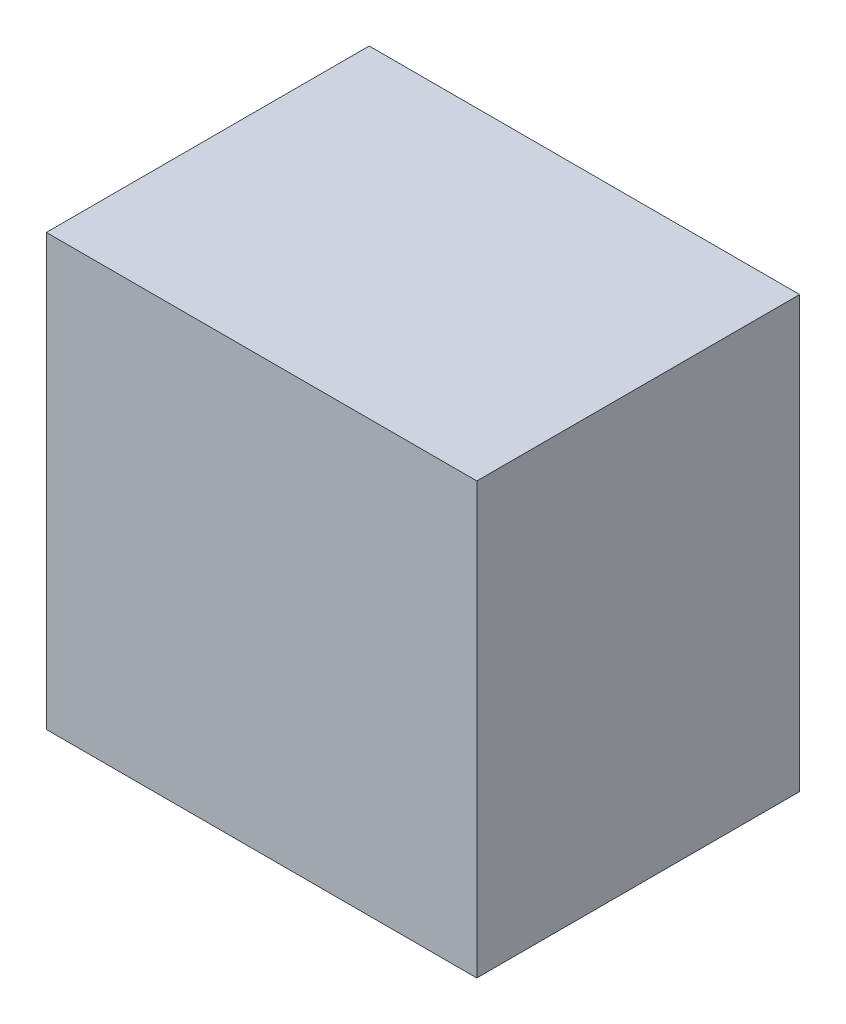
SolidWorks part; units mm, degrees
ref_plane "Front Plane" through (0, 0, 0) normal (0, 0, 1) x (1, 0, 0)
ref_plane "Top Plane" through (0, 0, 0) normal (0, 1, 0) x (1, 0, 0)
ref_plane "Right Plane" through (0, 0, 0) normal (1, 0, 0) x (0, 0, -1)
sketch "Sketch1" plane through (0, 0, 0) normal (0, 1, 0) x (1, 0, 0)
  line L0 (-20, -15) -> (20, -15)
  line L1 (20, -15) -> (20, 15)
  line L2 (20, 15) -> (-20, 15)
  line L3 (-20, 15) -> (-20, -15)
extrude "Boss-Extrude1" add sketch "Sketch1" along normal blind 40
